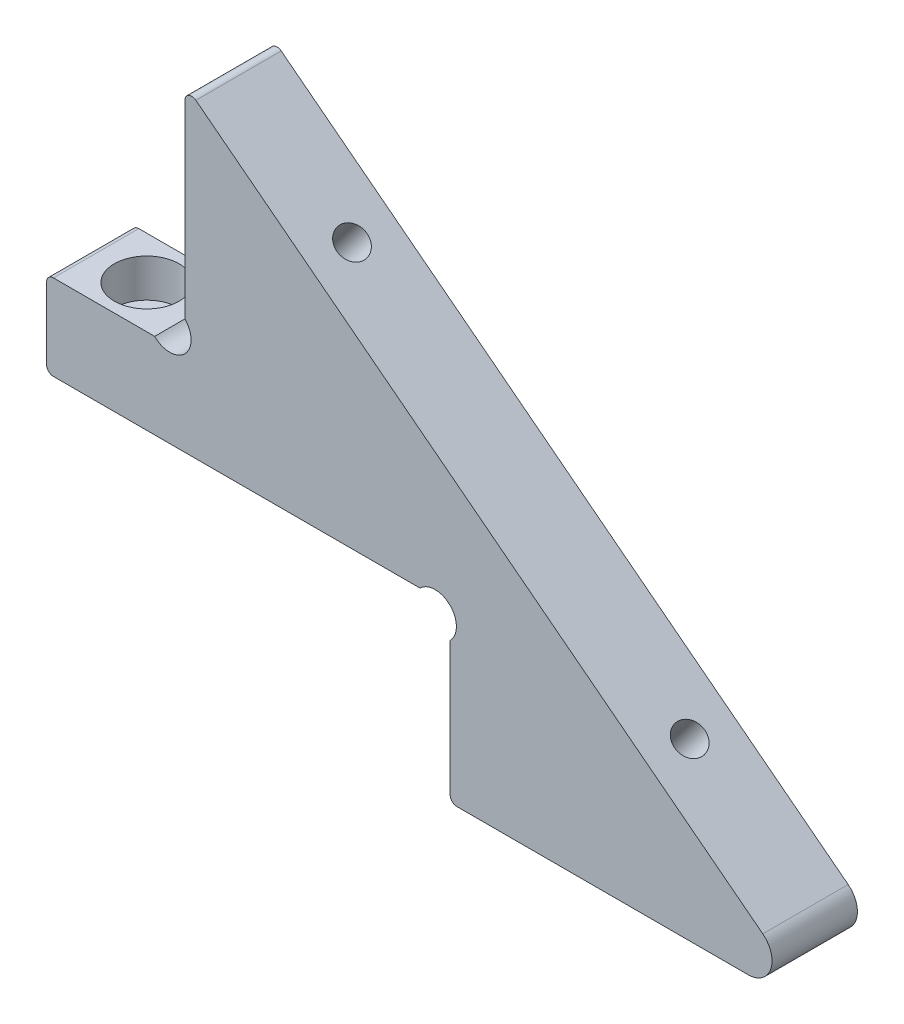
SolidWorks part; units mm, degrees
ref_plane "Front Plane" through (0, 0, 0) normal (0, 0, 1) x (1, 0, 0)
ref_plane "Top Plane" through (0, 0, 0) normal (0, 1, 0) x (1, 0, 0)
ref_plane "Right Plane" through (0, 0, 0) normal (1, 0, 0) x (0, 0, -1)
sketch "Model" plane through (0, 0, 0) normal (0, 0, 1) x (1, 0, 0)
  line L0 (-662.9283, 76.124) -> (-690.7004, 76.124)
  line L1 (-660.6832, 63.4241) -> (-638.5176, 63.4241)
  line L2 (-690.7004, 82.474) -> (-682.6617, 82.474)
  line L3 (-680.4166, 99.8446) -> (-680.4166, 84.7191)
  line L4 (-660.6832, 63.4241) -> (-660.6832, 73.879)
  line L5 (-660.6832, 76.124) -> (-666.1879, 70.6194) construction
  line L7 (-660.6832, 73.879) -> (-660.6832, 68.0149) construction
  line L8 (-662.9283, 76.124) -> (-666.1879, 76.124) construction
  line L9 (-660.6832, 73.879) -> (-660.6832, 70.6194) construction
  line L10 (-660.6832, 70.6194) -> (-666.1879, 70.6194) construction
  line L11 (-666.1879, 76.124) -> (-666.1879, 70.6194) construction
  line L16 (-690.7004, 82.474) -> (-690.7004, 76.124)
  line L18 (-680.4166, 82.474) -> (-683.3281, 85.3855) construction
  line L19 (-682.6617, 82.474) -> (-683.3281, 82.474) construction
  line L21 (-680.4166, 85.3855) -> (-683.3281, 85.3855) construction
  line L22 (-683.3281, 82.474) -> (-683.3281, 85.3855) construction
  line L49 (-680.4166, 99.8446) -> (-637.4313, 66.6047)
  arc A0 (-682.6617, 82.474) -> (-680.4166, 84.7191) centre (-681.5391, 83.5966) ccw
  arc A1 (-660.6832, 73.879) -> (-662.9283, 76.124) centre (-661.8058, 75.0015) ccw
  arc A2 (-638.5176, 63.4241) -> (-637.4313, 66.6047) centre (-638.5176, 65.1999) ccw
  dimension "D14" = 3.175
  dimension "D9" = 3.175
  dimension "D1" = 6.35
  dimension "D4" = 680.4166
  dimension "D5" = 683.3281
  dimension "D10" = 660.6832
  dimension "D15" = 10.2837
  dimension "D27" = 63.4241
extrude "Boss-Extrude1" add sketch "Model" along normal blind 6.35
fillet "Fillet1" radius 0.508 4 edges at (-660.6832, 63.4241, 3.175) (-690.7004, 76.124, 3.175) (-690.7004, 82.474, 3.175) (-680.4166, 99.8446, 3.175)
hole_wizard "CBORE for #4 Socket Head Cap Screw1" positions "Sketch1" profile "Sketch3" counterbore size "#4" standard "ANSI Inch" end condition through all
sketch "Sketch1" plane through (0, 82.474, 0) normal (0, 1, 0) x (1, 0, 0)
  line L1 (-690.1924, 0) -> (-682.6617, -6.35) construction
  point P16 (-686.427, -3.175)
sketch "Sketch3" plane through (-686.427, 82.474, 3.175) normal (1, 0, 0) x (0, 0, 1)
  line L0 (0, 0) -> (0, 19.05)
  line L1 (0, 19.05) -> (1.4732, 19.05)
  line L3 (1.4732, 19.05) -> (1.4732, 2.8448)
  line L4 (1.4732, 2.8448) -> (2.413, 2.8448)
  line L5 (2.413, 2.8448) -> (2.413, 0)
  line L7 (2.413, 0) -> (0, 0)
  line L11 (0, -6.35) -> (0, 107.95) construction
  dimension "Thru Hole Dia." = 2.9464
  dimension "Thru Hole Depth" = 19.05
  dimension "C'Bore Dia." = 4.826
  dimension "C'Bore Depth" = 2.8448
hole_wizard "Tap Drill for #4-40 Tap1" positions "Sketch6" profile "Sketch8" hole size "#4-40" standard "ANSI Inch"
sketch "Sketch6" plane through (-206.2993, -266.7831, 0) normal (0.6117, 0.7911, 0) x (0.7911, -0.6117, 0)
  point P3 (-555.8826, -3.175)
sketch "Sketch8" plane through (-646.0422, 73.2634, 3.175) normal (0, 0, 1) x (-0.7911, 0.6117, 0)
  line L0 (0, 0) -> (0, 8.0371)
  line L1 (0, 8.0371) -> (1.1303, 7.3579)
  line L2 (1.1303, 7.3579) -> (1.1303, 0)
  line L5 (1.1303, 0) -> (0, 0)
  line L10 (0, 8.0371) -> (-1.1303, 7.3579) construction
  line L11 (0, -6.35) -> (0, 107.95) construction
  dimension "Hole Dia." = 2.2606
  dimension "Hole Depth" = 7.3579
  dimension "Drill Angle" = 118
hole_wizard "Tap Drill for #4-40 Tap2" positions "Sketch9" profile "Sketch10" hole size "#4-40" standard "ANSI Inch"
sketch "Sketch9" plane through (-206.2993, -266.7831, 0) normal (0.6117, 0.7911, 0) x (0.7911, -0.6117, 0)
  point P0 (-587.6326, -3.175)
sketch "Sketch10" plane through (-671.1587, 92.6856, 3.175) normal (0, 0, 1) x (-0.7911, 0.6117, 0)
  line L0 (0, 0) -> (0, 8.9147)
  line L1 (0, 8.9147) -> (1.1303, 8.2356)
  line L2 (1.1303, 8.2356) -> (1.1303, 0)
  line L5 (1.1303, 0) -> (0, 0)
  line L10 (0, 8.9147) -> (-1.1303, 8.2356) construction
  line L11 (0, -6.35) -> (0, 107.95) construction
  dimension "Hole Dia." = 2.2606
  dimension "Hole Depth" = 8.2356
  dimension "Drill Angle" = 118
thread "Thread1" pitch 0.635 start angle 0, offset 0, length 0, pitch 0.635, diameter 2.2606
ref_plane "Plane1" through (-675.3024, 85.4792, 3.175) normal (0, 0, 1) x (0.7911, -0.6117, 0)
sketch "Thread Profile1" plane through (-675.3024, 85.4792, 3.175) normal (0, 0, 1) x (0.7911, -0.6117, 0)
  line L0 (0, 0) -> (0, 0.635) construction
  line L1 (0, 0) -> (0.3437, 0.1984)
  line L2 (0.3437, 0.1984) -> (0.3437, 0.2778)
  line L3 (0.3437, 0.2778) -> (0, 0.4762)
  line L4 (0.3437, 0.2381) -> (0, 0.2381) construction
  line L11 (0, 0) -> (0, 0.4762)
  point P2 (0, 0)
  dimension "Pitch" = 0.635
  dimension "Profile_Angle" = 60
  dimension "Profile_Land" = 0.0794
  dimension "Profile_Height" = 0.3437
thread "Thread2" pitch 0.635 start angle 0, offset 0.254, length 0, pitch 0.635, diameter 2.2606
ref_plane "Plane2" through (-649.8044, 66.5504, 3.175) normal (0, 0, 1) x (0.7911, -0.6117, 0)
sketch "Thread Profile2" plane through (-649.8044, 66.5504, 3.175) normal (0, 0, 1) x (0.7911, -0.6117, 0)
  line L0 (0, 0) -> (0, 0.635) construction
  line L1 (0, 0) -> (0.3437, 0.1984)
  line L2 (0.3437, 0.1984) -> (0.3437, 0.2778)
  line L3 (0.3437, 0.2778) -> (0, 0.4762)
  line L4 (0.3437, 0.2381) -> (0, 0.2381) construction
  line L11 (0, 0) -> (0, 0.4762)
  point P2 (0, 0)
  dimension "Pitch" = 0.635
  dimension "Profile_Angle" = 60
  dimension "Profile_Land" = 0.0794
  dimension "Profile_Height" = 0.3437
